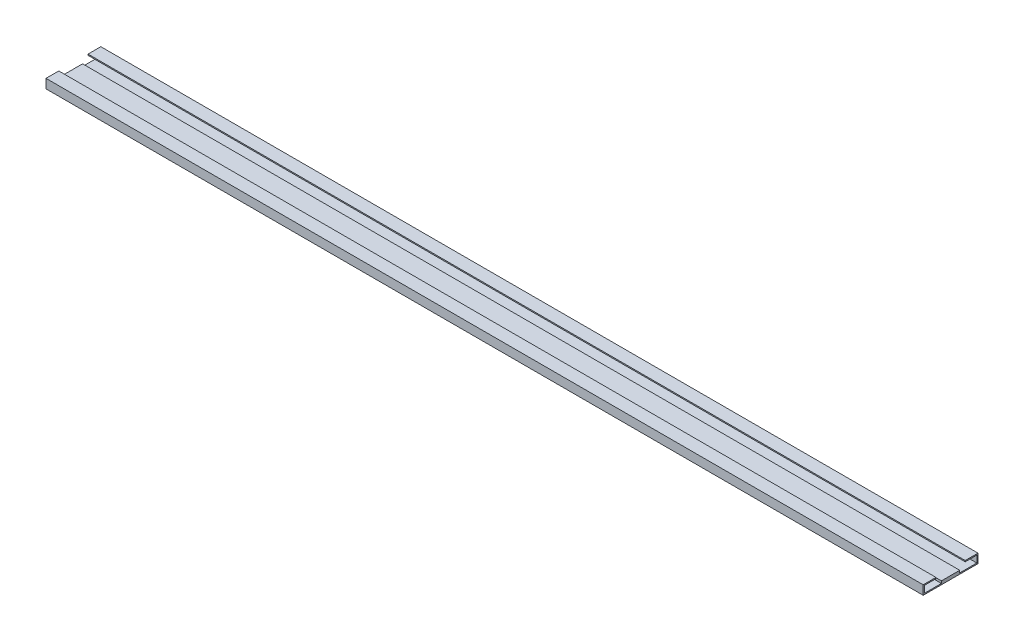
SolidWorks part; units mm, degrees
ref_plane "Front Plane" through (0, 0, 0) normal (0, 0, 1) x (1, 0, 0)
ref_plane "Top Plane" through (0, 0, 0) normal (0, 1, 0) x (1, 0, 0)
ref_plane "Right Plane" through (0, 0, 0) normal (1, 0, 0) x (0, 0, -1)
sketch "Sketch1" plane through (0, 0, 0) normal (0, 1, 0) x (1, 0, 0)
  line L1 (-304.8, -19.05) -> (304.8, -19.05)
  line L2 (-304.8, -19.05) -> (-304.8, 19.05)
  line L3 (-304.8, 19.05) -> (304.8, 19.05)
  line L4 (304.8, -19.05) -> (304.8, 19.05)
  line L5 (-304.8, -19.05) -> (304.8, 19.05) construction
  line L6 (-304.8, 19.05) -> (304.8, -19.05) construction
  point P0 (0, 0)
  dimension "D1" = 38.1
  dimension "D2" = 609.6
extrude "Boss-Extrude1" add sketch "Sketch1" along normal blind 6.35
sketch "Sketch2" plane through (-304.8, 0, 0) normal (-1, 0, 0) x (0, 0, 1)
  line L0 (-10.16, 6.35) -> (-10.16, 5.5562)
  line L1 (-19.05, 6.35) -> (19.05, 6.35) construction
  line L2 (-10.16, 5.5562) -> (-18.2563, 5.5562)
  line L3 (-18.2563, 5.5562) -> (-18.2563, 0.7937)
  line L4 (-18.2563, 0.7937) -> (-6.35, 0.7937)
  line L5 (-6.35, 0.7937) -> (-6.35, 2.3812)
  line L6 (-6.35, 2.3812) -> (6.35, 2.3812)
  line L7 (6.35, 2.3812) -> (6.35, 0.7937)
  line L8 (6.35, 0.7937) -> (18.2562, 0.7937)
  line L9 (18.2562, 0.7937) -> (18.2562, 5.5562)
  line L10 (18.2562, 5.5562) -> (10.16, 5.5562)
  line L11 (10.16, 5.5562) -> (10.16, 6.35)
  line L12 (10.16, 6.35) -> (-10.16, 6.35)
  line L13 (-19.05, 6.35) -> (-19.05, 0) construction
  line L14 (-19.05, 0) -> (19.05, 0) construction
  dimension "D1" = 0.7937
  dimension "D2" = 0.7937
  dimension "D3" = 0.7937
  dimension "D4" = 1.5875
  dimension "D5" = 12.7
  dimension "D6" = 11.9062
  dimension "D7" = 11.9062
  dimension "D8" = 0.7937
  dimension "D9" = 0.7937
  dimension "D10" = 3.81
  dimension "D11" = 3.81
extrude "Cut-Extrude1" cut sketch "Sketch2" against normal blind 609.6
